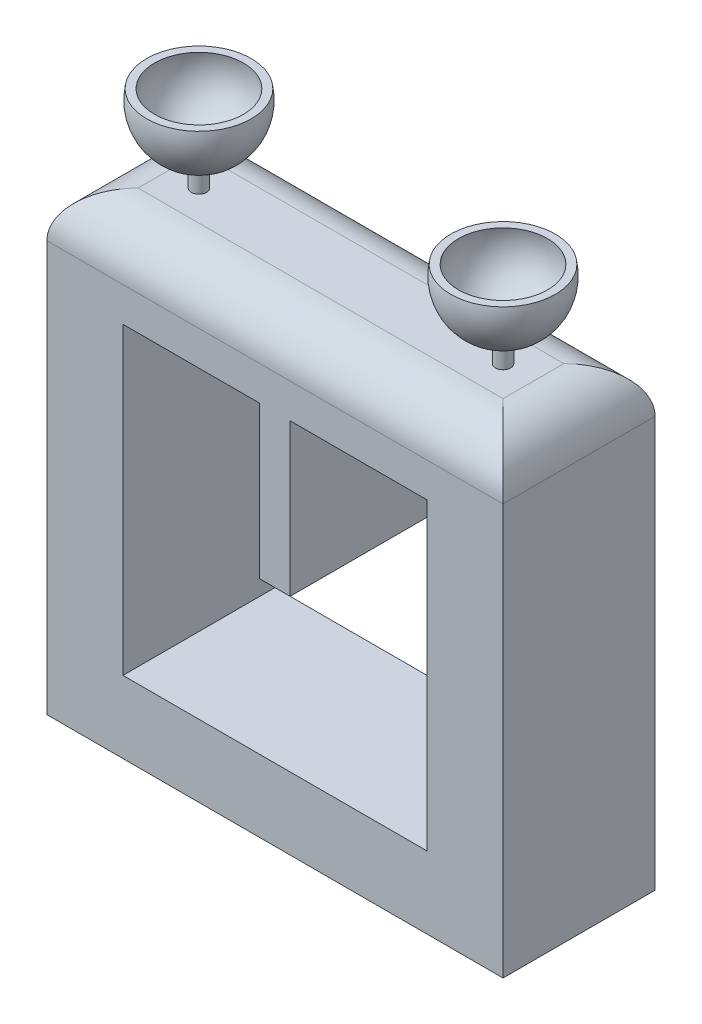
SolidWorks part; units mm, degrees
ref_plane "Front Plane" through (0, 0, 0) normal (0, 0, 1) x (1, 0, 0)
ref_plane "Top Plane" through (0, 0, 0) normal (0, 1, 0) x (1, 0, 0)
ref_plane "Right Plane" through (0, 0, 0) normal (1, 0, 0) x (0, 0, -1)
sketch "Sketch1" plane through (0, 0, 0) normal (0, 0, 1) x (1, 0, 0)
  line L1 (0, 0) -> (30, 0)
  line L2 (0, 0) -> (0, 30)
  line L3 (0, 30) -> (30, 30)
  line L4 (30, 0) -> (30, 30)
extrude "Boss-Extrude1" add sketch "Sketch1" along normal blind 10
fillet "Fillet1" radius 3 4 edges at (0, 30, 5) (15, 30, 0) (15, 30, 10) (30, 30, 5)
ref_plane "Plane1" through (5, 0, 0) normal (-1, 0, 0) x (0, 0, 1)
ref_plane "Plane2" through (15, 0, 0) normal (-1, 0, 0) x (0, 0, 1)
sketch "Sketch5" plane through (0, 0, 0) normal (0, 0, -1) x (-1, 0, 0)
  line L6 (-25, 24.7382) -> (-5, 24.7382)
  line L7 (-25, 24.7382) -> (-25, 4.7382)
  line L8 (-25, 4.7382) -> (-5, 4.7382)
  line L9 (-5, 24.7382) -> (-5, 4.7382)
extrude "Cut-Extrude1" cut sketch "Sketch5" against normal blind 21
sketch "Sketch6" plane through (0, 30, 0) normal (0, 1, 0) x (1, 0, 0)
  line L0 (5, 5.5) -> (5, -5.5) construction
  circle A0 centre (5, -5) radius 0.5
  dimension "D1" = 1
extrude "Boss-Extrude4" add sketch "Sketch6" along normal blind 2
sketch "Sketch7" plane through (5, 0, 0) normal (-1, 0, 0) x (0, 0, 1)
  line L1 (5.5, 32) -> (4.5, 32) construction
  line L2 (5, 32) -> (5, 31.5)
  line L4 (8.4371, 35.6608) -> (7.9263, 35.6608)
  arc A0 (5, 32) -> (7.9263, 35.6608) centre (5, 35) ccw
  arc A1 (5, 31.5) -> (8.4371, 35.6608) centre (5, 35) ccw
  dimension "D2" = 7
  dimension "D1" = 3
revolve "Revolve1" add sketch "Sketch7" angle 360 about L2
mirror "Mirror3" about plane through (15, 0, 0) normal (-1, 0, 0) of "Boss-Extrude4", "Revolve1"
sketch "Sketch9" plane through (0, 0, 10) normal (0, 0, 1) x (1, 0, 0)
  line L1 (13.9948, 24.7382) -> (13.9948, 14.7382)
  line L2 (15.9948, 24.7382) -> (15.9948, 14.7382)
  line L3 (13.9948, 24.7382) -> (15.9948, 24.7382)
  line L4 (13.9948, 14.7382) -> (15.9948, 14.7382)
extrude "Boss-Extrude6" add sketch "Sketch9" against normal blind 10
ref_plane "Plane5" through (0, 0, 5) normal (0, 0, 1) x (1, 0, 0)
